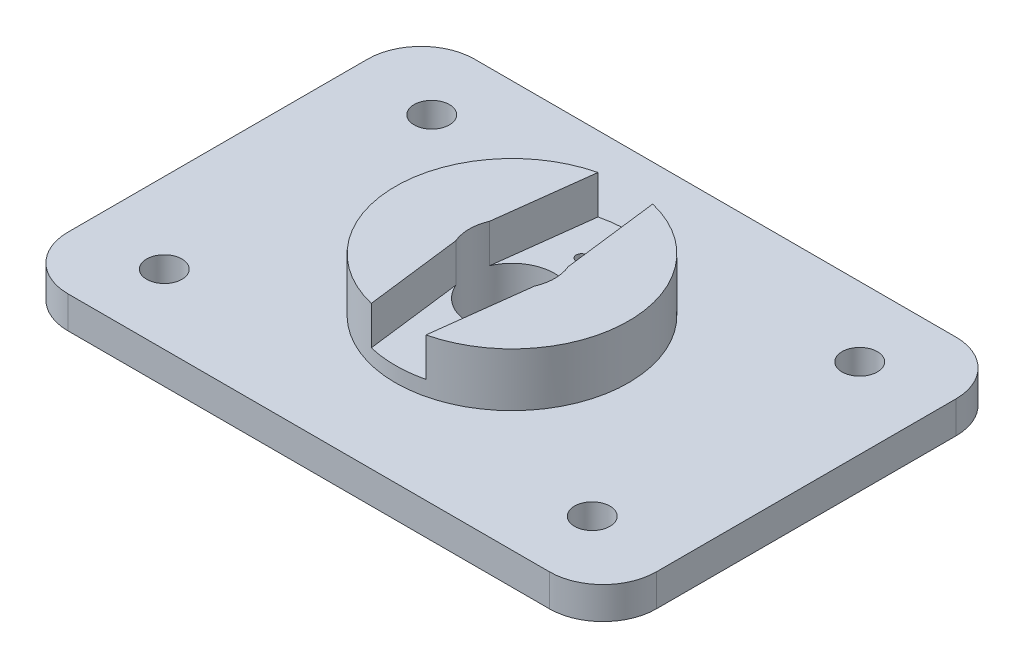
SolidWorks part; units mm, degrees
ref_plane "前视基准面" through (0, 0, 0) normal (0, 0, 1) x (1, 0, 0)
ref_plane "上视基准面" through (0, 0, 0) normal (0, 1, 0) x (1, 0, 0)
ref_plane "右视基准面" through (0, 0, 0) normal (1, 0, 0) x (0, 0, -1)
sketch "草图1" plane through (0, 0, 0) normal (0, 1, 0) x (1, 0, 0)
  line L1 (-27.5, 19) -> (27.5, 19)
  line L2 (-27.5, 19) -> (-27.5, -19)
  line L3 (-27.5, -19) -> (27.5, -19)
  line L4 (27.5, 19) -> (27.5, -19)
  line L5 (-27.5, 19) -> (27.5, -19) construction
  line L6 (-27.5, -19) -> (27.5, 19) construction
  point P0 (0, 0)
  dimension "D1" = 55
  dimension "D2" = 38
extrude "凸台-拉伸1" add sketch "草图1" along normal blind 3
sketch "草图2" plane through (0, 3, 0) normal (0, 1, 0) x (1, 0, 0)
  circle A0 centre (0, 0) radius 10.9
  dimension "D1" = 21.8
extrude "凸台-拉伸2" add sketch "草图2" along normal blind 5
sketch "草图3" plane through (0, 0, 0) normal (0, -1, 0) x (1, 0, 0)
  circle A0 centre (0, 0) radius 4
  dimension "D1" = 8
extrude "切除-拉伸1" cut sketch "草图3" against normal through all
sketch "草图4" plane through (0, 8, 0) normal (0, 1, 0) x (1, 0, 0)
  line L0 (3.6748, -1.5798) -> (2.3413, -12.3203)
  line L1 (0, -1000) -> (0, 49000) construction
  line L2 (-1000, 0) -> (49000, 0) construction
  line L3 (-3.6748, -1.5798) -> (-2.3413, -12.3203)
  line L4 (-3.6748, 1.5798) -> (-2.3413, 12.3203)
  line L5 (3.6748, 1.5798) -> (2.3413, 12.3203)
  line L6 (2.3413, -12.3203) -> (-2.3413, -12.3203)
  line L7 (2.3413, 12.3203) -> (-2.3413, 12.3203)
  line L8 (3.6748, -1.5798) -> (-3.6748, -1.5798)
  line L9 (3.6748, 1.5798) -> (-3.6748, 1.5798)
  circle A1 centre (0, 0) radius 4 construction
extrude "切除-拉伸2" cut sketch "草图4" against normal blind 3.6
sketch "草图5" plane through (0, 4.4, 0) normal (0, 1, 0) x (1, 0, 0)
  line L0 (-1.65, 0) -> (1.65, 0) construction
  circle A0 centre (0, -6.5) radius 0.5
  circle A1 centre (0, 6.5) radius 0.5
  dimension "D1" = 1
  dimension "D3" = 1
  dimension "D2" = 6.5
  dimension "D4" = 6.5
extrude "切除-拉伸3" cut sketch "草图5" against normal blind 4
fillet "圆角1" radius 5 1 edges at (27.5, 1.5, 19)
fillet "圆角2" radius 5 1 edges at (-27.5, 1.5, 19)
fillet "圆角3" radius 5 1 edges at (-27.5, 1.5, -19)
fillet "圆角4" radius 5 1 edges at (27.5, 1.5, -19)
sketch "草图6" plane through (0, 0, 0) normal (0, -1, 0) x (1, 0, 0)
  line L1 (-20, -12.5) -> (20, -12.5) construction
  line L2 (-20, -12.5) -> (-20, 12.5) construction
  line L3 (-20, 12.5) -> (20, 12.5) construction
  line L4 (20, -12.5) -> (20, 12.5) construction
  line L5 (-20, -12.5) -> (20, 12.5) construction
  line L6 (-20, 12.5) -> (20, -12.5) construction
  circle A0 centre (-20, 12.5) radius 1.65
  circle A1 centre (20, 12.5) radius 1.65
  circle A2 centre (20, -12.5) radius 1.65
  circle A3 centre (-20, -12.5) radius 1.65
  point P0 (0, 0)
  dimension "D3" = 3.3
  dimension "D1" = 40
  dimension "D2" = 25
extrude "切除-拉伸4" cut sketch "草图6" against normal through all
